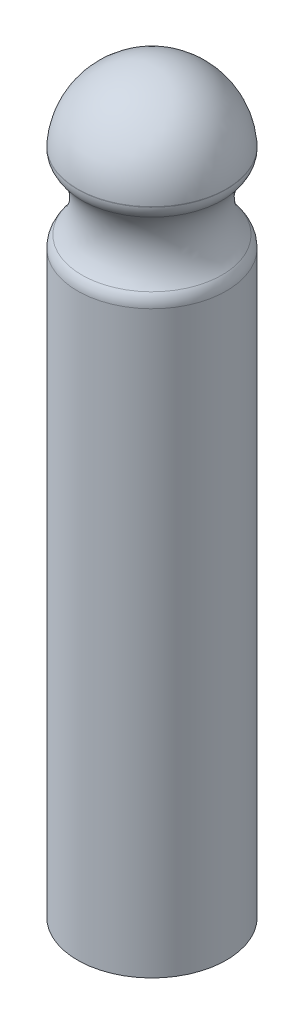
SolidWorks part; units mm, degrees
ref_plane "Front Plane" through (0, 0, 0) normal (0, 0, 1) x (1, 0, 0)
ref_plane "Top Plane" through (0, 0, 0) normal (0, 1, 0) x (1, 0, 0)
ref_plane "Right Plane" through (0, 0, 0) normal (1, 0, 0) x (0, 0, -1)
sketch "Sketch2" plane through (0, 0, 0) normal (0, 0, 1) x (1, 0, 0)
  line L0 (0, 0) -> (6.24, 0)
  line L3 (0, 61.8546) -> (0, 0) construction
  line L4 (0, 0) -> (0, 61.8546)
  line L6 (6.24, 55.9591) -> (6.24, 55.9985)
  line L8 (6.24, 48.5885) -> (6.24, 0)
  arc A1 (0, 61.8546) -> (6.24, 55.9985) centre (0, 55.602) cw
  arc A4 (5.8779, 54.9818) -> (5.8779, 49.5658) centre (9.0306, 52.2738) ccw
  arc A5 (6.24, 55.9591) -> (5.8779, 54.9818) centre (4.74, 55.9591) cw
  arc A6 (5.8779, 49.5658) -> (6.24, 48.5885) centre (4.74, 48.5885) cw
  point P11 (6.24, 54.3398)
  point P14 (6.24, 47.6694)
  dimension "D3" = 4.1561
  dimension "D2" = 1.5
  dimension "D5" = 5.8779
  dimension "D4" = 6.2526
  dimension "D8" = 48.5885
  dimension "D1" = 6.24
  dimension "D6" = 47.6694
  dimension "D7" = 55.602
  dimension "D11" = 54.3398
revolve "Revolve1" add sketch "Sketch2" angle 360 about L3
